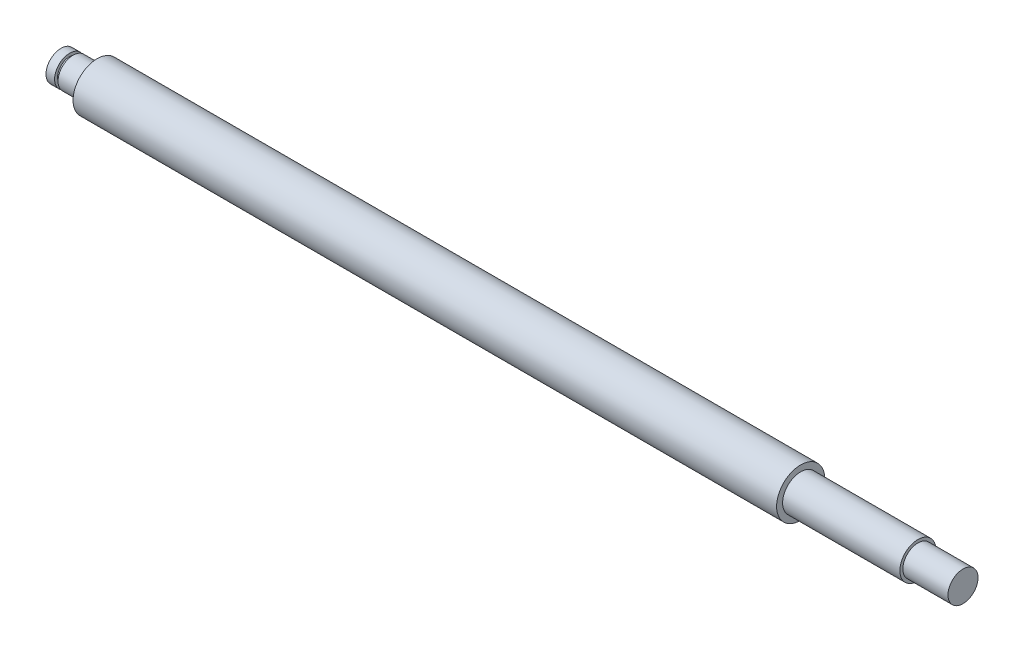
SolidWorks part; units mm, degrees
ref_plane "Plan de face" through (0, 0, 0) normal (0, 0, 1) x (1, 0, 0)
ref_plane "Plan de dessus" through (0, 0, 0) normal (0, 1, 0) x (1, 0, 0)
ref_plane "Plan de droite" through (0, 0, 0) normal (1, 0, 0) x (0, 0, -1)
sketch "Esquisse1" plane through (0, 0, 0) normal (0, 0, 1) x (1, 0, 0)
  line L0 (-89.4006, 0) -> (1216.033, 0) construction
  line L1 (-88.2233, 0) -> (-88.2233, 5)
  line L2 (-88.2233, 5) -> (-85.3699, 5)
  line L3 (-85.3699, 5) -> (-85.3699, 4)
  line L4 (-85.3699, 4) -> (-84.2199, 4)
  line L5 (-84.2199, 4) -> (-84.2199, 5)
  line L6 (-84.2199, 5) -> (-76.2199, 5)
  line L7 (-76.2199, 5) -> (-76.2199, 8)
  line L8 (-76.2199, 8) -> (157.7801, 8)
  line L9 (157.7801, 8) -> (157.7801, 6)
  line L10 (157.7801, 6) -> (184.7801, 6)
  line L11 (184.7801, 6) -> (196.7801, 6)
  line L12 (196.7801, 6) -> (196.7801, 5)
  line L13 (196.7801, 5) -> (211.7801, 5)
  line L14 (211.7801, 5) -> (211.7801, 0)
  line L15 (-88.2233, 0) -> (211.7801, 0)
  dimension "D1" = 5
  dimension "D2" = 2.8534
  dimension "D3" = 1
  dimension "D4" = 1.15
  dimension "D5" = 8
  dimension "D6" = 3
  dimension "D7" = 1
  dimension "D8" = 234
  dimension "D9" = 2
  dimension "D10" = 27
  dimension "D11" = 12
  dimension "D12" = 1
  dimension "D13" = 15
  dimension "D14" = 5
revolve "Révolution1" add sketch "Esquisse1" angle 360 about L0
